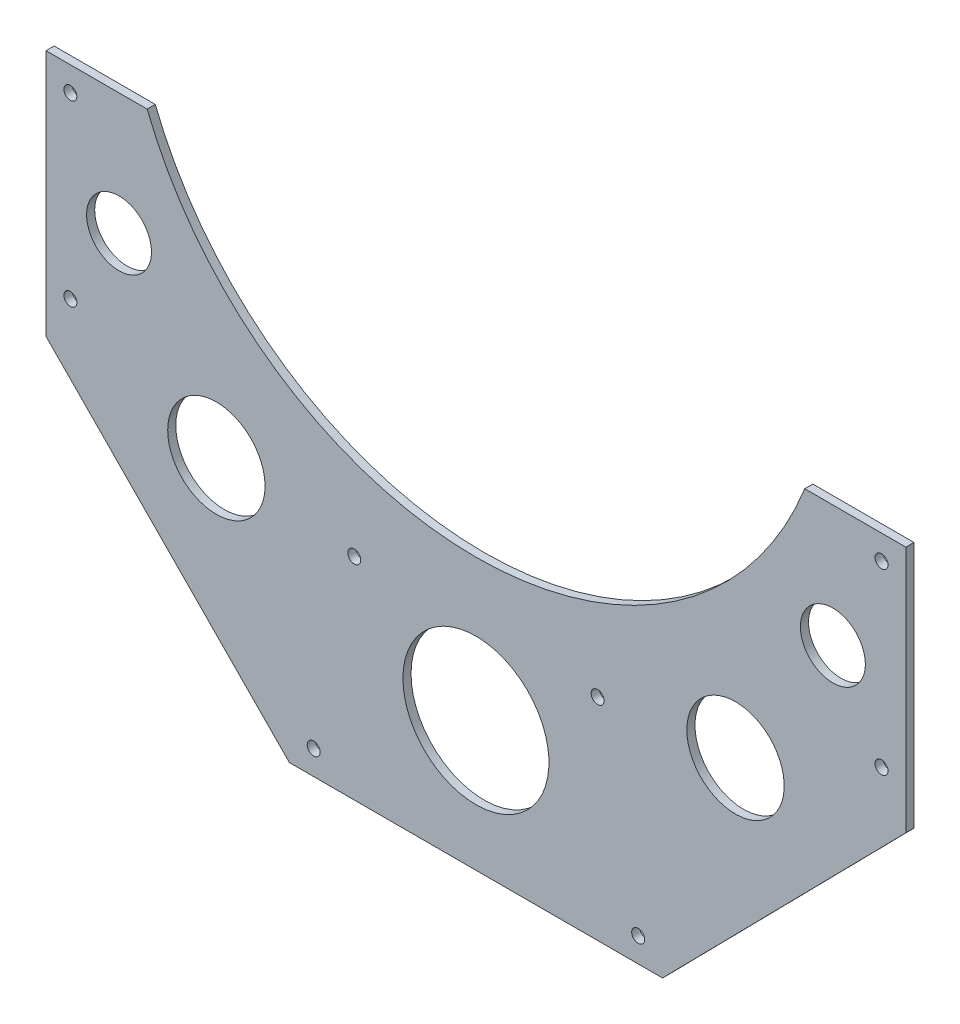
SolidWorks part; units mm, degrees
material "Q235"
ref_plane "前视基准面" through (0, 0, 0) normal (0, 0, 1) x (1, 0, 0)
ref_plane "上视基准面" through (0, 0, 0) normal (0, 1, 0) x (1, 0, 0)
ref_plane "右视基准面" through (0, 0, 0) normal (1, 0, 0) x (0, 0, -1)
sketch "草图1" plane through (0, 0, 0) normal (0, 0, 1) x (1, 0, 0)
  line L1 (0, 0) -> (1060, 0)
  line L2 (0, 0) -> (0, 610)
  line L3 (0, 610) -> (1060, 610)
  line L4 (1060, 0) -> (1060, 610)
  dimension "D1" = 1060
  dimension "D2" = 610
extrude "凸台-拉伸1" add sketch "草图1" along normal blind 10
sketch "草图3" plane through (0, 0, 10) normal (0, 0, 1) x (1, 0, 0)
  line L0 (0, 305) -> (300, 0)
  line L1 (0, 610) -> (0, 0) construction
  line L2 (0, 0) -> (1060, 0) construction
  line L3 (300, 0) -> (0, 0)
  line L4 (0, 0) -> (0, 305)
  line L5 (1060, 305) -> (760, 0)
  line L6 (1060, 0) -> (1060, 610) construction
  line L7 (760, 0) -> (1060, 0)
  line L8 (1060, 0) -> (1060, 305)
  line L9 (1060, 610) -> (0, 610) construction
  line L10 (1060, 610) -> (0, 610) construction
  line L12 (935.3123, 610) -> (124.6877, 610)
  line L14 (530, 0) -> (530, 610) construction
  arc A0 (124.6877, 610) -> (935.3123, 610) centre (530, 770) ccw
  point P23 (530, 334.25)
  dimension "D3" = 871.5
  dimension "D1" = 300
  dimension "D2" = 300
  dimension "D4" = 160
  dimension "D5" = 160
extrude "切除-拉伸2" cut sketch "草图3" against normal blind 10
hole_wizard "Ø16.0 (16) 直径孔1" positions "草图4" profile "草图5" hole size "Ø16.0" standard "GB"
sketch "草图4" plane through (0, 0, 0) normal (0, 0, -1) x (-1, 0, 0)
  line L0 (-530, 770) -> (-530, -88.0082) construction
  line L2 (-1060, 610) -> (-935.3123, 610) construction
  line L3 (-300, 0) -> (-760, 0) construction
  point P0 (-1030, 580)
  point P2 (-1030, 360)
  point P4 (-730, 30)
  point P6 (-330, 30)
  point P8 (-30, 360)
  point P10 (-30, 580)
  point P23 (-680, 260)
  point P25 (-380, 260)
  dimension "D1" = 500
  dimension "D2" = 250
  dimension "D3" = 30
  dimension "D4" = 200
  dimension "D5" = 30
  dimension "D6" = 150
  dimension "D7" = 260
sketch "草图5" plane through (1030, 580, 0) normal (1, 0, 0) x (0, 1, 0)
  line L0 (0, 0) -> (0, 46.8069)
  line L1 (0, 46.8069) -> (8, 42)
  line L2 (8, 42) -> (8, 0)
  line L5 (8, 0) -> (0, 0)
  line L10 (0, 46.8069) -> (-8, 42) construction
  line L11 (0, -6.35) -> (0, 107.95) construction
  dimension "孔直径" = 16
  dimension "孔深度" = 42
  dimension "导头角度" = 118
sketch "草图6" plane through (0, 0, 0) normal (0, 0, -1) x (-1, 0, 0)
  line L0 (-530, 770) -> (-530, -143.0872) construction
  line L1 (-124.6877, 610) -> (0, 610) construction
  circle A0 centre (-970, 460) radius 40
  circle A1 centre (-850, 280) radius 60
  circle A2 centre (-530, 160) radius 90
  circle A3 centre (-210, 280) radius 60
  circle A4 centre (-90, 460) radius 40
  point P13 (-530, 149.4924)
  dimension "D1" = 80
  dimension "D2" = 80
  dimension "D6" = 120
  dimension "D8" = 120
  dimension "D9" = 180
  dimension "D3" = 150
  dimension "D4" = 440
  dimension "D5" = 320
  dimension "D7" = 330
  dimension "D10" = 450
extrude "切除-拉伸3" cut sketch "草图6" against normal through all
